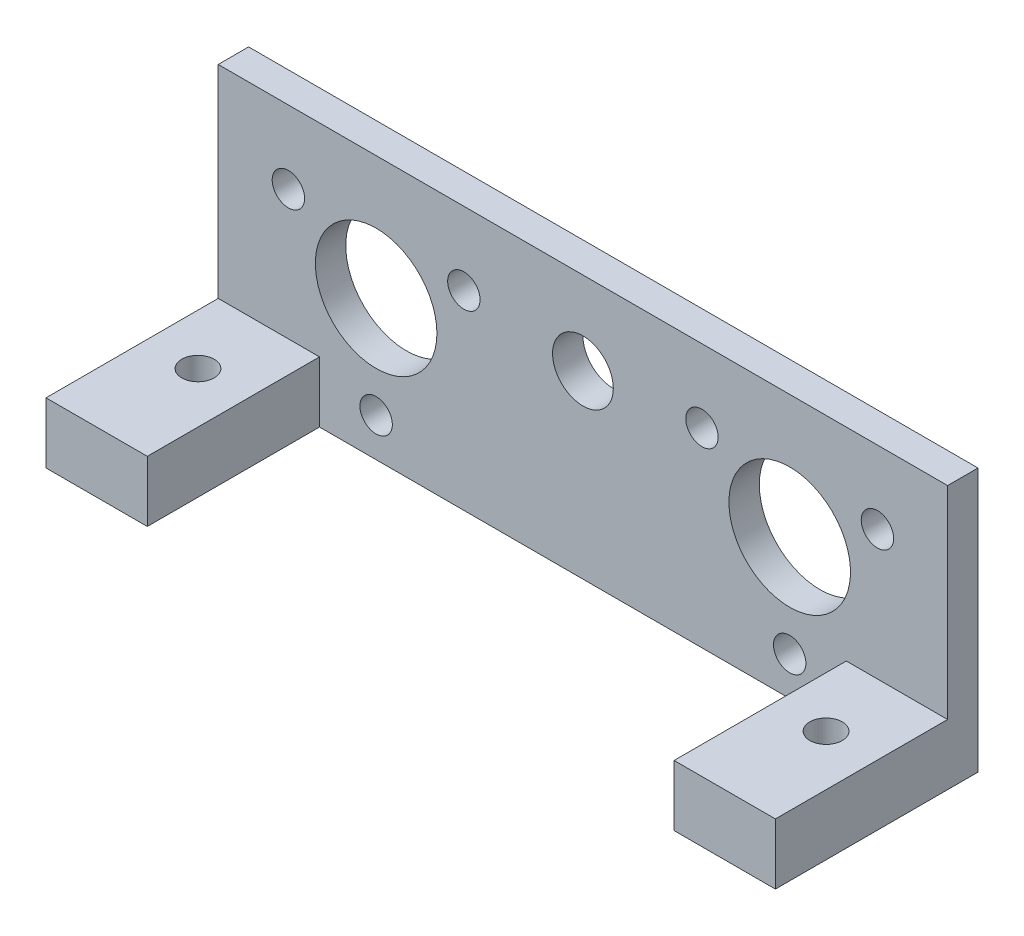
SolidWorks part; units mm, degrees
ref_plane "정면" through (0, 0, 0) normal (0, 0, 1) x (1, 0, 0)
ref_plane "윗면" through (0, 0, 0) normal (0, 1, 0) x (1, 0, 0)
ref_plane "우측면" through (0, 0, 0) normal (1, 0, 0) x (0, 0, -1)
sketch "스케치1" plane through (0, 0, 0) normal (0, 0, 1) x (1, 0, 0)
  line L0 (-10.2059, -2) -> (0, 0) construction
  line L1 (18, -10.5) -> (23.0493, -10.5) construction
  line L2 (-18, -8.9) -> (18, -8.9)
  line L3 (-18, -8.9) -> (-18, 4.1)
  line L4 (-18, 4.1) -> (18, 4.1)
  line L5 (18, 4.1) -> (18, -8.9)
  line L6 (23.0493, -10.5) -> (23.0493, -8.9) construction
  line L7 (0, 0) -> (0, 17.3457) construction
  line L8 (23.0493, -8.9) -> (-29.249, -8.9) construction
  line L9 (-10.2059, -7) -> (-10.2059, -2) construction
  line L10 (-10.2059, -2) -> (-5.8758, 0.5) construction
  line L11 (-10.2059, -2) -> (-14.536, 0.5) construction
  line L12 (10.2059, -2) -> (10.2059, -7) construction
  circle A0 centre (0, 0) radius 12.5 construction
  circle A1 centre (-10.2059, -2) radius 8.5 construction
  circle A2 centre (-10.2059, -2) radius 3
  circle A3 centre (-10.2059, -2) radius 5 construction
  circle A4 centre (-14.536, 0.5) radius 0.8
  circle A5 centre (-5.8758, 0.5) radius 0.8
  circle A6 centre (0, 0) radius 1.5
  circle A7 centre (-10.2059, -7) radius 0.8
  circle A8 centre (10.2059, -2) radius 5 construction
  circle A9 centre (10.2059, -2) radius 8.5 construction
  circle A10 centre (10.2059, -7) radius 0.8
  circle A11 centre (5.8758, 0.5) radius 0.8
  circle A12 centre (14.536, 0.5) radius 0.8
  circle A13 centre (10.2059, -2) radius 3
  circle A14 centre (-10.2059, -2) radius 2 construction
  circle A15 centre (0, 0) radius 8.75 construction
  point P12 (-10.2059, -2)
  point P13 (0, -12.5)
  point P15 (-15.1698, -8.9)
  point P34 (-5.242, -8.9)
  point P35 (5.242, -8.9)
  point P36 (15.1698, -8.9)
  point P40 (-8.5846, -1.6823)
  point P41 (-8.2432, -1.6154)
  dimension "D1" = 25
  dimension "D2" = 3
  dimension "D6" = 1.6
  dimension "D7" = 10
  dimension "D8" = 17
  dimension "D9" = 12.758
  dimension "D10" = 2.8302
  dimension "D3" = 2.8302
  dimension "D5" = 6
  dimension "D13" = 0.3479
  dimension "D4" = 1.6
  dimension "D11" = 12.758
  dimension "D12" = 10.484
extrude "돌출1" add sketch "스케치1" along normal blind 1.5
sketch "스케치2" plane through (0, 0, 1.5) normal (0, 0, 1) x (1, 0, 0)
  line L0 (-18, -5.9) -> (-13, -5.9)
  line L1 (-18, 4.1) -> (-18, -8.9) construction
  line L2 (-13, -8.9) -> (-13, -5.9)
  line L3 (-18, -8.9) -> (18, -8.9) construction
  line L4 (0, 0) -> (0, 9.781) construction
  line L5 (13, -8.9) -> (13, -5.9)
  line L6 (18, -5.9) -> (13, -5.9)
extrude "돌출2" add sketch "스케치2" along normal blind 8.5
hole_wizard "M2 탭을 위한 탭 드릴1" positions "3D 스케치1" profile "스케치3" hole size "M2x0.4" standard "Ansi 미터법" end condition up to next
sketch3d "3D 스케치1"
  line L0 (-15.5, -8.9, 10) -> (-15.5, -8.9, -0.5928) construction
  line L1 (-18, -8.9, 10) -> (-13, -8.9, 10) construction
  line L4 (-18, -8.9, 5) -> (18, -8.9, 5) construction
  line L5 (-18, -8.9, 10) -> (-18, -8.9, 0) construction
  line L6 (18, -8.9, 10) -> (18, -8.9, 0) construction
  line L9 (15.5, -8.9, 10) -> (15.5, -8.9, -0.81) construction
  line L10 (13, -8.9, 10) -> (18, -8.9, 10) construction
  point P0 (-15.5, -8.9, 5)
  point P2 (15.5, -8.9, 5)
sketch "스케치3" plane through (-15.5, -8.9, 5) normal (1, 0, 0) x (0, 0, -1)
  line L0 (0, 0) -> (0, 3)
  line L1 (0, 3) -> (0.8, 3)
  line L2 (0.8, 3) -> (0.8, 0)
  line L5 (0.8, 0) -> (0, 0)
  line L11 (0, -6.35) -> (0, 107.95) construction
  dimension "관통 구멍 지름" = 1.6
  dimension "관통 구멍 깊이" = 3
